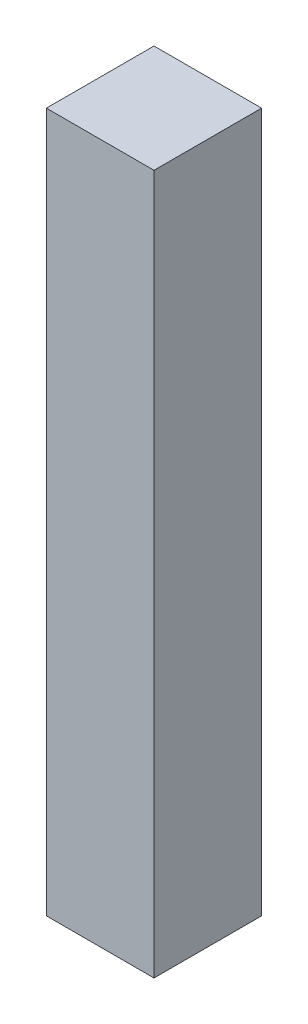
SolidWorks part; units mm, degrees
material "Balsa"
ref_plane "Alzado" through (0, 0, 0) normal (0, 0, 1) x (1, 0, 0)
ref_plane "Planta" through (0, 0, 0) normal (0, 1, 0) x (1, 0, 0)
ref_plane "Vista lateral" through (0, 0, 0) normal (1, 0, 0) x (0, 0, -1)
sketch "Croquis1" plane through (0, 0, 0) normal (0, 1, 0) x (1, 0, 0)
  line L1 (-2.5, -2.5) -> (2.5, -2.5)
  line L2 (-2.5, -2.5) -> (-2.5, 2.5)
  line L3 (-2.5, 2.5) -> (2.5, 2.5)
  line L4 (2.5, -2.5) -> (2.5, 2.5)
  line L5 (-2.5, -2.5) -> (2.5, 2.5) construction
  line L6 (-2.5, 2.5) -> (2.5, -2.5) construction
  point P0 (0, 0)
  dimension "D1" = 5
  dimension "D2" = 5
extrude "Saliente-Extruir1" add sketch "Croquis1" along normal mid plane 32.5
